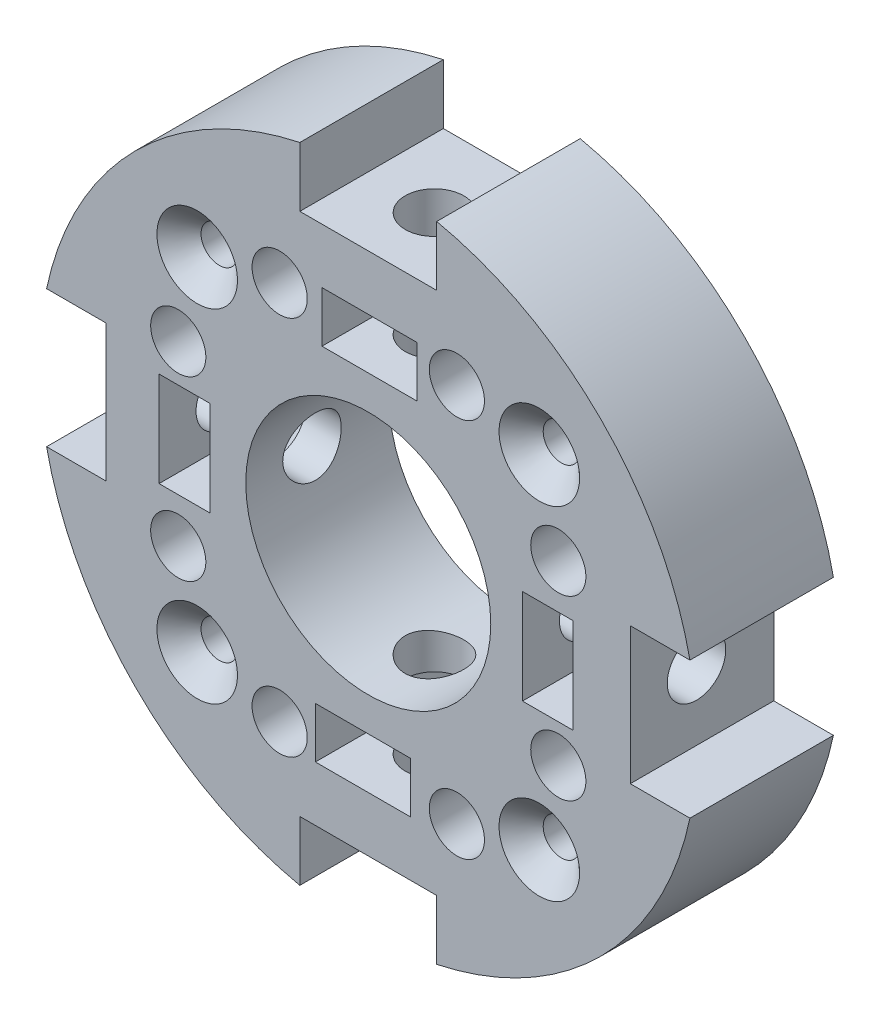
SolidWorks part; units mm, degrees
ref_plane "Plan de face" through (0, 0, 0) normal (0, 0, 1) x (1, 0, 0)
ref_plane "Plan de dessus" through (0, 0, 0) normal (0, 1, 0) x (1, 0, 0)
ref_plane "Plan de droite" through (0, 0, 0) normal (1, 0, 0) x (0, 0, -1)
sketch "Esquisse1" plane through (0, 0, 0) normal (0, 0, 1) x (1, 0, 0)
  line L36 (-18.9562, 4.6) -> (-14.3562, 4.6)
  line L52 (-0.2997, 0.2997) -> (-35355.6388, 35355.6388) construction
  line L54 (0, -1000) -> (0, 49000) construction
  line L60 (6, 23.9414) -> (6, 29.3939) construction
  line L61 (-14.3562, -4) -> (-14.3562, 4.6)
  line L62 (-18.6562, -3.7) -> (-14.6562, -3.7) construction
  line L63 (-18.6562, -3.7) -> (-18.6562, 4.3) construction
  line L64 (-18.6562, 4.3) -> (-14.6562, 4.3) construction
  line L65 (-14.6562, -3.7) -> (-14.6562, 4.3) construction
  line L66 (-18.6562, -3.7) -> (-14.6562, 4.3) construction
  line L67 (-23.9414, -6) -> (-29.3939, -6) construction
  line L68 (-23.9414, -6) -> (-23.9414, 6) construction
  line L69 (-23.9414, 6) -> (-29.3939, 6) construction
  line L71 (-6, 23.9414) -> (6, 23.9414) construction
  line L72 (-6, 23.9414) -> (-6, 29.3939)
  line L73 (-4.2406, 9.094) -> (-21135.1537, 45324.4833) construction
  line L74 (-23.7414, -6.2) -> (-23.7414, 6.2)
  line L75 (-23.7414, 6.2) -> (-29.1479, 6.2)
  line L76 (-6.2, 23.7414) -> (-6.2, 29.1479)
  line L77 (-18.6562, 4.3) -> (-14.6562, -3.7) construction
  line L78 (-18.9562, -4) -> (-14.3562, -4)
  line L79 (-18.9562, -4) -> (-18.9562, 4.6)
  line L80 (4.4068, 18.7629) -> (4.4068, 14.1629)
  line L81 (-4.1932, 14.1629) -> (4.4068, 14.1629)
  line L82 (-4.1932, 18.7629) -> (-4.1932, 14.1629)
  line L83 (-4.1932, 18.7629) -> (4.4068, 18.7629)
  line L84 (18.5697, -4.6) -> (13.9697, -4.6)
  line L85 (13.9697, 4) -> (13.9697, -4.6)
  line L86 (18.5697, 4) -> (13.9697, 4)
  line L87 (18.5697, 4) -> (18.5697, -4.6)
  line L88 (-4.7932, -18.7629) -> (-4.7932, -14.1629)
  line L89 (3.8068, -14.1629) -> (-4.7932, -14.1629)
  line L90 (3.8068, -18.7629) -> (3.8068, -14.1629)
  line L91 (3.8068, -18.7629) -> (-4.7932, -18.7629)
  line L92 (23.9414, -6) -> (29.3939, -6) construction
  line L93 (23.9414, 6) -> (23.9414, -6) construction
  line L94 (23.9414, 6) -> (29.3939, 6) construction
  line L95 (-6, -23.9414) -> (-6, -29.3939) construction
  line L96 (6, -23.9414) -> (-6, -23.9414) construction
  line L97 (6, -23.9414) -> (6, -29.3939) construction
  line L98 (-6.2, 23.7414) -> (6.2, 23.7414)
  line L99 (6.2, 23.7414) -> (6.2, 29.1479)
  line L100 (23.7414, 6.2) -> (29.1479, 6.2)
  line L101 (23.7414, 6.2) -> (23.7414, -6.2)
  line L102 (23.7414, -6.2) -> (29.1479, -6.2)
  line L103 (6.2, -23.7414) -> (6.2, -29.1479)
  line L104 (6.2, -23.7414) -> (-6.2, -23.7414)
  line L105 (-6.2, -23.7414) -> (-6.2, -29.1479)
  line L106 (-23.7414, -6.2) -> (-29.1479, -6.2)
  circle A1 centre (0, 0) radius 11.1
  circle A2 centre (-15.5, 15.5) radius 1.65
  circle A3 centre (15.5, 15.5) radius 1.65
  circle A4 centre (15.5, -15.5) radius 1.65
  circle A5 centre (-15.5, -15.5) radius 1.65
  arc A18 (-29.3939, -6) -> (-6, -29.3939) centre (0, 0) ccw construction
  circle A21 centre (-8.0297, 17.2198) radius 2.5
  arc A23 (-6, 29.3939) -> (-29.3939, 6) centre (0, 0) ccw construction
  arc A24 (29.3939, 6) -> (6, 29.3939) centre (0, 0) ccw construction
  arc A25 (6, -29.3939) -> (29.3939, -6) centre (0, 0) ccw construction
  circle A26 centre (8.0297, 17.2198) radius 2.5
  circle A27 centre (17.2198, 8.0297) radius 2.5
  circle A28 centre (17.2198, -8.0297) radius 2.5
  circle A29 centre (8.0297, -17.2198) radius 2.5
  circle A30 centre (-8.0297, -17.2198) radius 2.5
  circle A31 centre (-17.2198, -8.0297) radius 2.5
  circle A32 centre (-17.2198, 8.0297) radius 2.5
  arc A33 (-6.2, 29.1479) -> (-29.1479, 6.2) centre (0, 0) ccw
  arc A34 (29.1479, 6.2) -> (6.2, 29.1479) centre (0, 0) ccw
  arc A35 (6.2, -29.1479) -> (29.1479, -6.2) centre (0, 0) ccw
  arc A36 (-29.1479, -6.2) -> (-6.2, -29.1479) centre (0, 0) ccw
  point P1 (-27.9414, 0)
  point P22 (0, 0)
  point P32 (0, 0)
  point P33 (0, 0)
  point P39 (-16.6562, 0.3)
  point P73 (0, 0)
  point P75 (0, 0)
  point P90 (0, 0)
  dimension "D2" = 22.2
  dimension "D7" = 3.3
  dimension "D14" = 0.2
  dimension "D18" = 8
  dimension "D6" = 5.4525
  dimension "D15" = 5
  dimension "D4" = 60
  dimension "D11" = 4
  dimension "D3" = 12
  dimension "D5" = 21.9203
  dimension "D9" = 0.3
  dimension "D10" = 4
  dimension "D16" = 45
  dimension "D17" = 19
  dimension "D19" = 4
  dimension "D12" = 25
  dimension "D8" = 4
  dimension "D13" = 4
extrude "Boss.-Extru.1" add sketch "Esquisse1" along normal blind 13
chamfer "Chanfrein1" distance 2 angle 45 4 edges at (-13.85, -15.5, 13) (17.15, -15.5, 13) (17.15, 15.5, 13) (-13.85, 15.5, 13)
sketch "Esquisse2" plane through (-14.3562, 0, 0) normal (-1, 0, 0) x (0, 0, 1)
  line L1 (13, -6.2) -> (13, 6.2) construction
  circle A0 centre (7, 0) radius 2.65
  dimension "D1" = 5.3
  dimension "D2" = 6
extrude "Enlèv. mat.-Extru.1" cut sketch "Esquisse2" against normal up to next and the other way through all
pattern_circular "Répétition circulaire1" count 4 over 360 of "Enlèv. mat.-Extru.1"
